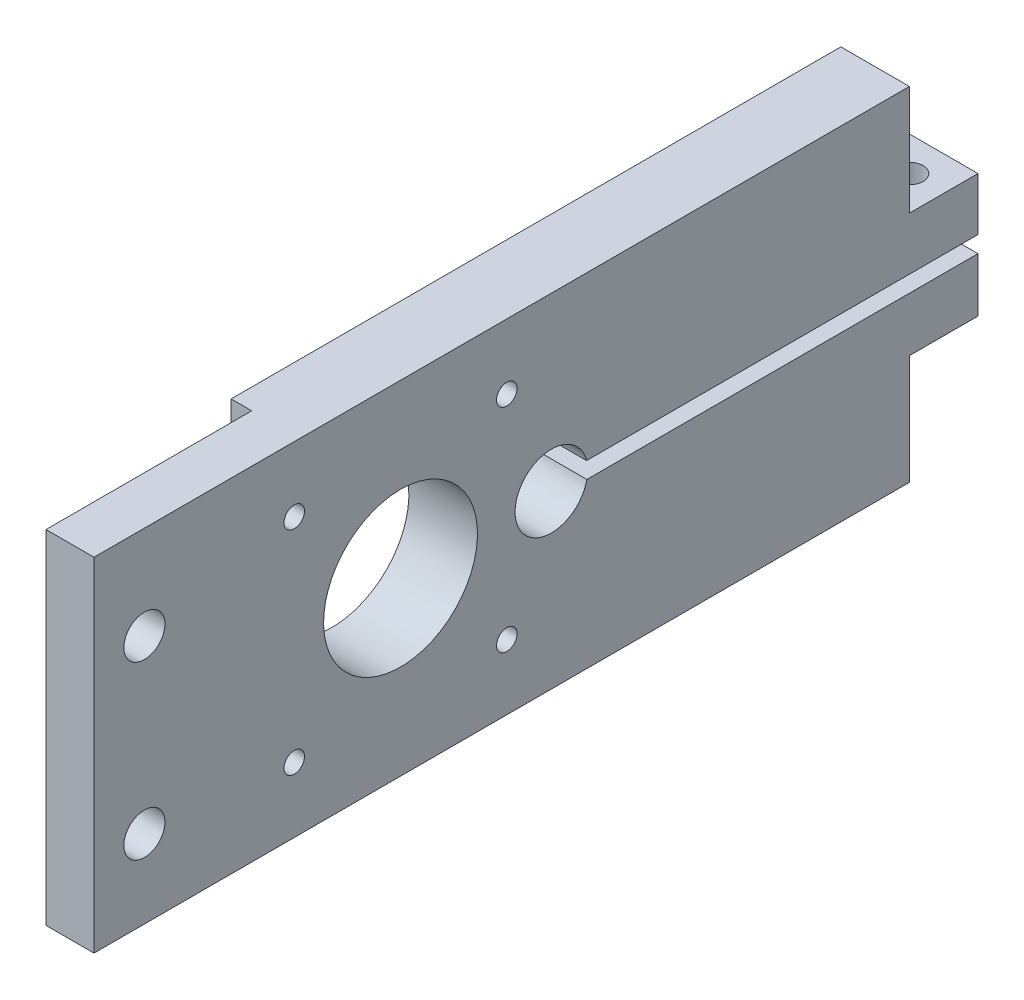
SolidWorks part; units mm, degrees
ref_plane "前视基准面" through (0, 0, 0) normal (0, 0, 1) x (1, 0, 0)
ref_plane "上视基准面" through (0, 0, 0) normal (0, 1, 0) x (1, 0, 0)
ref_plane "右视基准面" through (0, 0, 0) normal (1, 0, 0) x (0, 0, -1)
sketch "草图1" plane through (66, 0, 0) normal (1, 0, 0) x (0, 0, -1)
  line L0 (48, 250) -> (-3, 250) construction
  line L1 (-25.1133, 275) -> (120.7243, 275) construction
  line L2 (48, 300) -> (-3, 300) construction
  line L3 (48, 250) -> (-3, 250)
  line L5 (48, 300) -> (-3, 300)
  line L6 (48, 300) -> (108.2165, 300)
  line L7 (108.2165, 300) -> (108.2165, 250)
  line L8 (-530, 250) -> (150, 250) construction
  line L9 (108.2165, 250) -> (48, 250)
  line L10 (-3, 300) -> (-17.7022, 300)
  line L11 (-17.7022, 300) -> (-17.7022, 250)
  line L12 (-17.7022, 250) -> (-3, 250)
  line L13 (-10.3511, 300) -> (-10.3511, 250) construction
  circle A0 centre (42.5, 259.5) radius 1.5 construction
  circle A1 centre (42.5, 290.5) radius 1.5 construction
  circle A2 centre (11.5, 259.5) radius 1.5 construction
  circle A3 centre (11.5, 290.5) radius 1.5 construction
  circle A4 centre (42.5, 259.5) radius 1.5
  circle A5 centre (42.5, 290.5) radius 1.5
  circle A6 centre (11.5, 259.5) radius 1.5
  circle A7 centre (11.5, 290.5) radius 1.5
  circle A9 centre (49, 275) radius 5.2955
  circle A10 centre (-10.3511, 286.4017) radius 3
  circle A11 centre (-10.3511, 261.4017) radius 3
  circle A12 centre (27, 275) radius 11.2233 construction
  circle A13 centre (27, 275) radius 11.2233
  dimension "D2" = 6
  dimension "D3" = 6
  dimension "D4" = 25
  dimension "D8" = 10.5909
  dimension "D1" = 14.7022
  dimension "D5" = 13.5983
  dimension "D6" = 22
  dimension "D7" = 125.9187
extrude "凸台-拉伸1" add sketch "草图1" along normal blind 10
sketch "草图3" plane through (0, 250, 0) normal (0, -1, 0) x (1, 0, 0)
  line L0 (69, 17.7022) -> (69, -12.2978)
  line L1 (76, 17.7022) -> (66, 17.7022) construction
  line L2 (69, -12.2978) -> (66, -12.2978)
  line L3 (66, 17.7022) -> (66, -108.2165) construction
  line L4 (66, -12.2978) -> (66, 17.7022)
  line L5 (66, 17.7022) -> (69, 17.7022)
  dimension "D1" = 30
  dimension "D2" = 3
extrude "切除-拉伸2" cut sketch "草图3" against normal blind 50
sketch "草图4" plane through (76, 0, 0) normal (1, 0, 0) x (0, 0, -1)
  line L0 (109.5274, 275) -> (32.889, 275) construction
  line L1 (108.2165, 276.2897) -> (49.5274, 276.2897)
  line L3 (108.2165, 250) -> (108.2165, 300) construction
  line L4 (49.5274, 276.2897) -> (49.5274, 273.8856)
  line L5 (49.5274, 273.8856) -> (109.5274, 273.8856)
  line L6 (109.5274, 273.8856) -> (109.5274, 276.2897)
  line L7 (109.5274, 276.2897) -> (108.2165, 276.2897)
  circle A1 centre (49, 275) radius 5.2955 construction
  point P17 (78.055, 275.6608)
  dimension "D1" = 60
  dimension "D2" = 2.4041
  dimension "D3" = 1.3109
  dimension "D4" = 1.2897
  dimension "D5" = 1.2897
extrude "切除-拉伸3" cut sketch "草图4" against normal blind 10
sketch "草图5" plane through (0, 0, -108.2165) normal (0, 0, -1) x (-1, 0, 0)
  line L0 (-66, 250) -> (-66, 273.8856) construction
  line L2 (-76, 273.8856) -> (-76, 250) construction
  line L3 (-76, 250) -> (-66, 250) construction
  line L4 (-76, 300) -> (-76, 276.2897) construction
  line L6 (-66, 276.2897) -> (-66, 300) construction
  line L7 (-66, 300) -> (-76, 300) construction
  line L8 (-66, 250) -> (-66, 273.8856)
  line L9 (-66, 273.8856) -> (-76, 273.8856)
  line L10 (-76, 273.8856) -> (-76, 250)
  line L11 (-76, 250) -> (-66, 250)
  line L12 (-76, 300) -> (-76, 276.2897)
  line L13 (-76, 276.2897) -> (-66, 276.2897)
  line L14 (-66, 276.2897) -> (-66, 300)
  line L15 (-66, 300) -> (-76, 300)
extrude "凸台-拉伸2" add sketch "草图5" along normal blind 3
sketch "草图6" plane through (0, 300, 0) normal (0, 1, 0) x (1, 0, 0)
  line L0 (76, 106.2165) -> (66, 106.2165) construction
  line L1 (76, 111.2165) -> (76, -17.7022) construction
  line L2 (66, 111.2165) -> (66, 12.2978) construction
  line L3 (66, 111.2165) -> (76, 111.2165) construction
  circle A0 centre (71, 106.2165) radius 3.5
  dimension "D2" = 7
  dimension "D1" = 5
extrude "切除-拉伸4" cut sketch "草图6" against normal blind 5
sketch "草图7" plane through (0, 295, 0) normal (0, 1, 0) x (1, 0, 0)
  circle A0 centre (71, 106.2165) radius 2
  dimension "D1" = 4
extrude "切除-拉伸5" cut sketch "草图7" against normal blind 45
sketch "草图8" plane through (66, 0, 0) normal (-1, 0, 0) x (0, 0, 1)
  line L1 (-111.2165, 300) -> (-101.2165, 300)
  line L2 (-111.2165, 300) -> (-111.2165, 284)
  line L3 (-111.2165, 284) -> (-101.2165, 284)
  line L4 (-101.2165, 300) -> (-101.2165, 284)
  line L5 (-111.2165, 250) -> (-101.2165, 250)
  line L6 (-111.2165, 250) -> (-111.2165, 266)
  line L7 (-111.2165, 266) -> (-101.2165, 266)
  line L8 (-101.2165, 250) -> (-101.2165, 266)
  dimension "D1" = 10
  dimension "D2" = 10
  dimension "D3" = 16
  dimension "D4" = 16
extrude "切除-拉伸6" cut sketch "草图8" against normal blind 10
